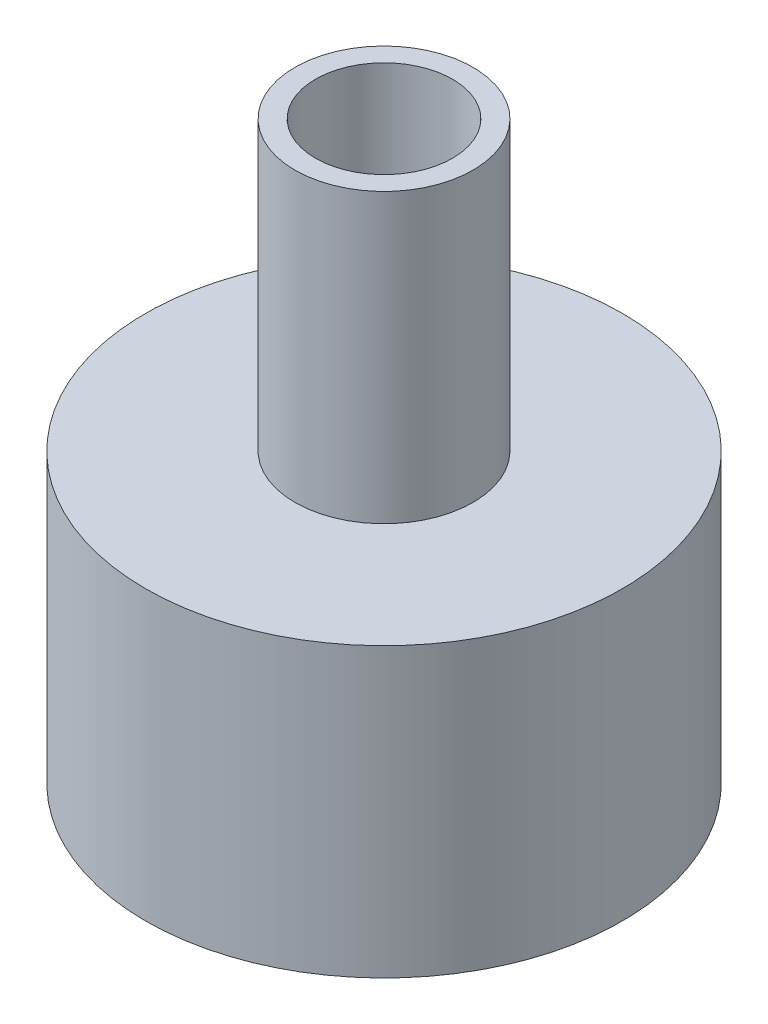
SolidWorks part; units mm, degrees
material "BUTYL"
ref_plane "Front Plane" through (0, 0, 0) normal (0, 0, 1) x (1, 0, 0)
ref_plane "Top Plane" through (0, 0, 0) normal (0, 1, 0) x (1, 0, 0)
ref_plane "Right Plane" through (0, 0, 0) normal (1, 0, 0) x (0, 0, -1)
sketch "Sketch2" plane through (0, 0, 0) normal (0, 1, 0) x (1, 0, 0)
  circle A0 centre (0, 0) radius 1.74
extrude "Boss-Extrude1" add sketch "Sketch2" along normal blind 2.1
sketch "Sketch3" plane through (0, 2.1, 0) normal (0, 1, 0) x (1, 0, 0)
  circle A0 centre (0, 0) radius 0.65
extrude "Boss-Extrude2" add sketch "Sketch3" along normal blind 2.1
sketch "Sketch4" plane through (0, 4.2, 0) normal (0, 1, 0) x (1, 0, 0)
  circle A0 centre (0, 0) radius 0.5
extrude "Cut-Extrude1" cut sketch "Sketch4" against normal blind 3.85
